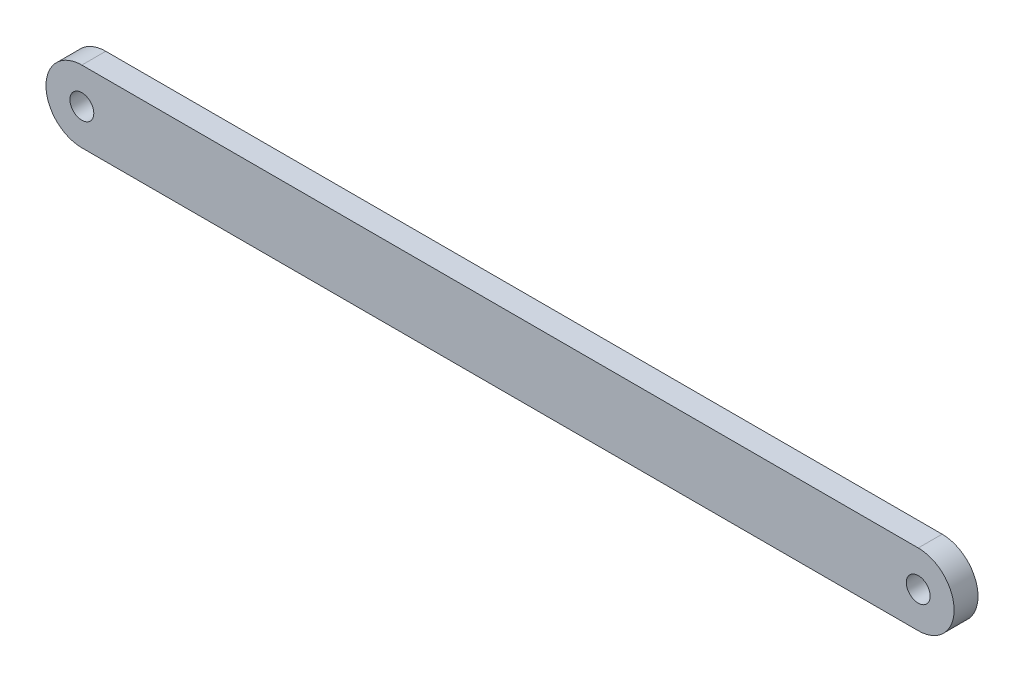
SolidWorks part; units mm, degrees
ref_plane "Ön Düzlem" through (0, 0, 0) normal (0, 0, 1) x (1, 0, 0)
ref_plane "Üst Düzlem" through (0, 0, 0) normal (0, 1, 0) x (1, 0, 0)
ref_plane "Sağ Düzlem" through (0, 0, 0) normal (1, 0, 0) x (0, 0, -1)
sketch "Çizim1" plane through (0, 0, 0) normal (0, 0, 1) x (1, 0, 0)
  line L0 (-175, 0) -> (175, 0) construction
  line L1 (-175, 15) -> (175, 15)
  line L2 (-175, -15) -> (175, -15)
  arc A0 (-175, 15) -> (-175, -15) centre (-175, 0) ccw
  arc A1 (175, -15) -> (175, 15) centre (175, 0) ccw
  circle A2 centre (175, 0) radius 5
  circle A3 centre (-175, 0) radius 5
  point P2 (0, 0)
  dimension "D2" = 10
  dimension "D3" = 15
  dimension "D4" = 10
  dimension "D1" = 350
extrude "Yükseklik-Ekstrüzyon1" add sketch "Çizim1" along normal mid plane 10 contours L2 A1 L1 A0
